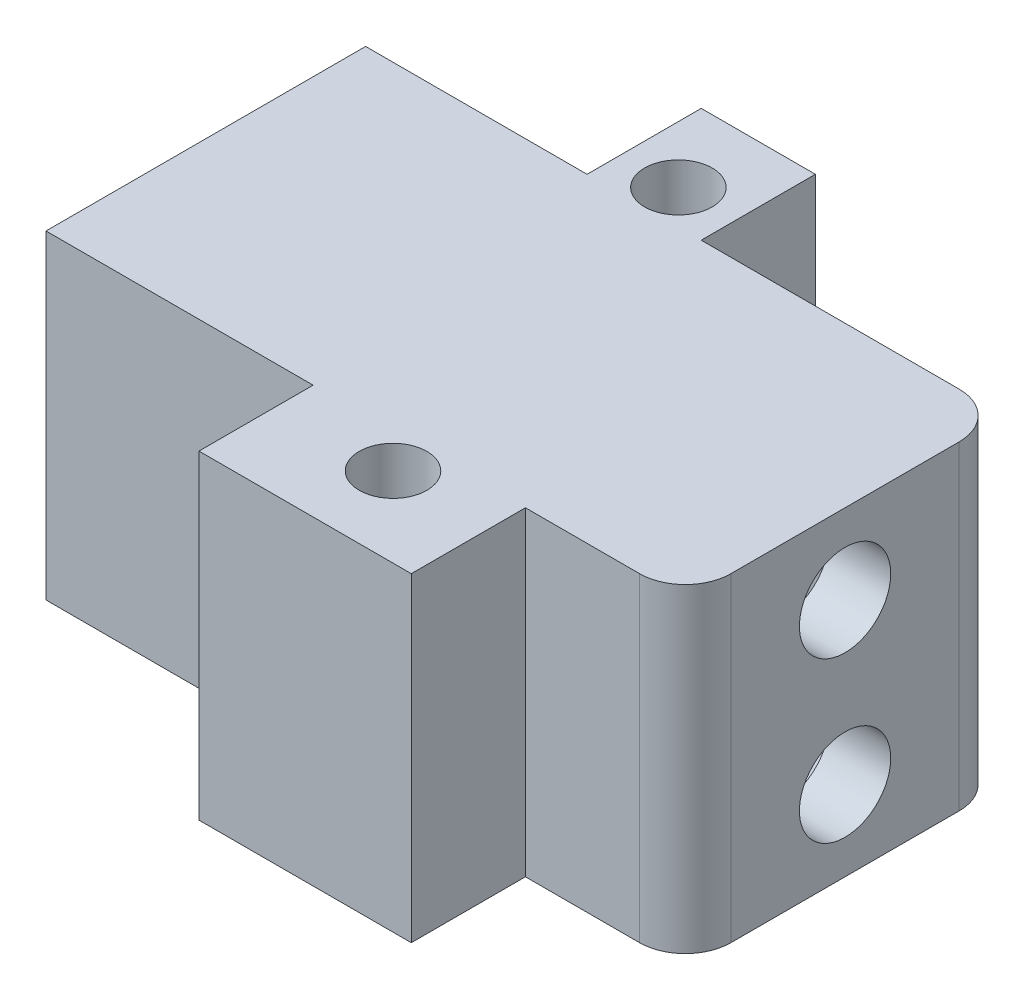
SolidWorks part; units mm, degrees
ref_plane "前视基准面" through (0, 0, 0) normal (0, 0, 1) x (1, 0, 0)
ref_plane "上视基准面" through (0, 0, 0) normal (0, 1, 0) x (1, 0, 0)
ref_plane "右视基准面" through (0, 0, 0) normal (1, 0, 0) x (0, 0, -1)
sketch "草图1" plane through (0, 0, 0) normal (0, 1, 0) x (1, 0, 0)
  line L1 (-14, 7) -> (14, 7)
  line L2 (-14, 7) -> (-14, -7)
  line L3 (-14, -7) -> (14, -7)
  line L4 (14, 7) -> (14, -7)
  line L5 (-14, 7) -> (14, -7) construction
  line L6 (-14, -7) -> (14, 7) construction
  point P0 (0, 0)
  dimension "D1" = 28
  dimension "D2" = 14
extrude "凸台-拉伸1" add sketch "草图1" along normal blind 14
sketch "草图2" plane through (-14, 0, 0) normal (-1, 0, 0) x (0, 0, 1)
  line L0 (-7, 14) -> (7, 0) construction
  line L1 (-7, 0) -> (7, 14) construction
  line L3 (-5, 13) -> (5, 13)
  line L4 (-7, 0) -> (7, 0)
  line L5 (7, 0) -> (7, 14)
  line L6 (7, 14) -> (-7, 14)
  line L7 (-7, 14) -> (-7, 0)
  line L8 (-7, 0) -> (7, 0)
  line L9 (7, 0) -> (7, 14)
  line L10 (7, 14) -> (-7, 14)
  line L11 (-7, 14) -> (-7, 0)
  line L12 (-5, 13) -> (-5, 1)
  line L13 (-5, 1) -> (5, 1)
  line L14 (5, 13) -> (5, 1)
  line L15 (-5, 13) -> (5, 1) construction
  line L16 (-5, 1) -> (5, 13) construction
  point P2 (0, 7)
  dimension "D2" = 12
  dimension "D3" = 10
  dimension "D1" = 0
extrude "切除-拉伸1" cut sketch "草图2" against normal blind 25.3 contours L12 L3 L14 L13
sketch "草图3" plane through (14, 0, 0) normal (1, 0, 0) x (0, 0, -1)
  line L0 (0, 14) -> (0, 0) construction
  line L2 (-7, 7) -> (7, 7)
  line L3 (-7, 7) -> (-7, 5.5)
  line L4 (-7, 0) -> (7, 0)
  line L5 (7, 0) -> (7, 14)
  line L6 (7, 14) -> (-7, 14)
  line L7 (-7, 14) -> (-7, 0)
  line L8 (-7, 0) -> (7, 0)
  line L9 (7, 0) -> (7, 14)
  line L10 (7, 14) -> (-7, 14)
  line L11 (-7, 14) -> (-7, 0)
  line L12 (-7, 5.5) -> (7, 5.5)
  line L13 (7, 7) -> (7, 5.5)
  line L14 (-7, 7) -> (7, 5.5) construction
  line L15 (-7, 5.5) -> (7, 7) construction
  circle A0 centre (0, 10.5) radius 2
  circle A1 centre (0, 3.5) radius 2
  point P10 (0, 6.25)
  dimension "D2" = 3.5
  dimension "D3" = 3.5
  dimension "D4" = 7
  dimension "D5" = 1.5
  dimension "D1" = 0
extrude "切除-拉伸2" cut sketch "草图3" against normal blind 25.5 contours A0 | A1
fillet "圆角4" radius 2 2 edges at (14, 7, -7) (14, 7, 7)
sketch "草图4" plane through (0, 0, 7) normal (0, 0, 1) x (1, 0, 0)
  line L0 (-14, 0) -> (12, 0) construction
  line L1 (-2.3, 0) -> (7, 0)
  line L2 (-2.3, 0) -> (-2.3, 14)
  line L3 (-2.3, 14) -> (7, 14)
  line L4 (7, 0) -> (7, 14)
  line L5 (-14, 14) -> (12, 14) construction
  line L6 (12, 0) -> (12, 14) construction
  dimension "D1" = 5
  dimension "D2" = 9.3
extrude "凸台-拉伸2" add sketch "草图4" along normal blind 5
sketch "草图5" plane through (0, 0, -7) normal (0, 0, -1) x (-1, 0, 0)
  line L1 (-0.7, 18) -> (-0.7, 13.5) construction
  line L2 (-0.7, 14) -> (4.3, 14)
  line L3 (-0.7, 14) -> (-0.7, 0)
  line L4 (14, 14) -> (-12, 14)
  line L5 (-12, 14) -> (-12, 0)
  line L6 (-12, 0) -> (14, 0)
  line L7 (14, 0) -> (14, 14)
  line L8 (14, 14) -> (-12, 14)
  line L9 (-12, 14) -> (-12, 0)
  line L10 (-12, 0) -> (14, 0)
  line L11 (14, 0) -> (14, 14)
  line L12 (-0.7, 0) -> (4.3, 0)
  line L13 (4.3, 14) -> (4.3, 0)
  line M7 (14, 14) -> (-12, 14)
  line M9 (-12, 0) -> (14, 0)
  dimension "D2" = 11.3
  dimension "D3" = 5
  dimension "D1" = 0
extrude "凸台-拉伸3" add sketch "草图5" along normal blind 5 contours L13 L3 M7 M9
sketch "草图6" plane through (0, 14, 0) normal (0, 1, 0) x (1, 0, 0)
  line L10 (-3.2378, 118.5) -> (-10.8877, 105.25)
  line L11 (-10.8877, 101.25) -> (-0.8, 83.7776)
  line L12 (14, -5) -> (14, 5)
  line L13 (12, 7) -> (0.7, 7)
  line L14 (0.7, 7) -> (0.7, 12)
  line L15 (0.7, 12) -> (-4.3, 12)
  line L16 (-4.3, 12) -> (-4.3, 7)
  line L17 (-4.3, 7) -> (-14, 7)
  line L18 (-14, 7) -> (-14, -7)
  line L19 (-14, -7) -> (-2.3, -7)
  line L20 (-2.3, -7) -> (-2.3, -12)
  line L21 (-2.3, -12) -> (7, -12)
  line L22 (7, -12) -> (7, -7)
  line L23 (7, -7) -> (12, -7)
  line L24 (14, -5) -> (14, 5)
  line L25 (12, 7) -> (0.7, 7)
  line L26 (0.7, 7) -> (0.7, 12)
  line L27 (0.7, 12) -> (-4.3, 12)
  line L28 (-4.3, 12) -> (-4.3, 7)
  line L29 (-4.3, 7) -> (-14, 7)
  line L30 (-14, 7) -> (-14, -7)
  line L31 (-14, -7) -> (-2.3, -7)
  line L32 (-2.3, -7) -> (-2.3, -12)
  line L33 (-2.3, -12) -> (7, -12)
  line L34 (7, -12) -> (7, -7)
  line L35 (7, -7) -> (12, -7)
  line L36 (-2.2641, 78.3135) -> (-9.3, 74.2513)
  line L37 (-9.3, 31.5) -> (-9.3, -15.5)
  line L38 (-9.3, -15.5) -> (52.7, -15.5)
  line L39 (52.7, -15.5) -> (52.7, 31.5)
  line L40 (52.7, 74.2513) -> (45.6641, 78.3135)
  line L41 (44.2, 83.7776) -> (54.2877, 101.25)
  line L42 (54.2877, 105.25) -> (46.6378, 118.5)
  line L43 (46.6378, 118.5) -> (-3.2378, 118.5)
  line L44 (-3.2378, 118.5) -> (-10.8877, 105.25)
  line L45 (-10.8877, 101.25) -> (-0.8, 83.7776)
  line L46 (-2.2641, 78.3135) -> (-9.3, 74.2513)
  line L47 (-9.3, 31.5) -> (-9.3, -15.5)
  line L48 (-9.3, -15.5) -> (52.7, -15.5)
  line L49 (52.7, -15.5) -> (52.7, 31.5)
  line L50 (52.7, 74.2513) -> (45.6641, 78.3135)
  line L51 (44.2, 83.7776) -> (54.2877, 101.25)
  line L52 (54.2877, 105.25) -> (46.6378, 118.5)
  line L53 (46.6378, 118.5) -> (-3.2378, 118.5)
  line L186 (-9.3, 74.2513) -> (-15.3, 71.5)
  line L187 (-9.3, 74.2513) -> (-15.3, 71.5)
  line L188 (-15.3, 71.5) -> (-15.3, 31.5)
  line L189 (-15.3, 71.5) -> (-15.3, 31.5)
  line L190 (-15.3, 31.5) -> (-9.3, 31.5)
  line L191 (-15.3, 31.5) -> (-9.3, 31.5)
  line L192 (52.7, 31.5) -> (58.7, 31.5)
  line L193 (52.7, 31.5) -> (58.7, 31.5)
  line L194 (58.7, 31.5) -> (58.7, 71.5)
  line L195 (58.7, 31.5) -> (58.7, 71.5)
  line L196 (58.7, 71.5) -> (52.7, 74.2513)
  line L197 (58.7, 71.5) -> (52.7, 74.2513)
  circle A0 centre (2.7, -8.5) radius 1.48
  arc A2 (14, 5) -> (12, 7) centre (12, 5) ccw
  arc A3 (12, -7) -> (14, -5) centre (12, -5) ccw
  arc A4 (14, 5) -> (12, 7) centre (12, 5) ccw
  arc A5 (12, -7) -> (14, -5) centre (12, -5) ccw
  circle A7 centre (-1.8, 8.5) radius 1.48 construction
  arc A8 (-10.8877, 105.25) -> (-10.8877, 101.25) centre (-7.4236, 103.25) ccw
  arc A9 (-2.2641, 78.3135) -> (-0.8, 83.7776) centre (-4.2641, 81.7776) ccw
  arc A10 (44.2, 83.7776) -> (45.6641, 78.3135) centre (47.6641, 81.7776) ccw
  arc A11 (54.2877, 101.25) -> (54.2877, 105.25) centre (50.8236, 103.25) ccw
  arc A12 (-10.8877, 105.25) -> (-10.8877, 101.25) centre (-7.4236, 103.25) ccw
  arc A13 (-2.2641, 78.3135) -> (-0.8, 83.7776) centre (-4.2641, 81.7776) ccw
  arc A14 (44.2, 83.7776) -> (45.6641, 78.3135) centre (47.6641, 81.7776) ccw
  arc A15 (54.2877, 101.25) -> (54.2877, 105.25) centre (50.8236, 103.25) ccw
  circle A16 centre (-1.8, 8.5) radius 1.48
  dimension "D3" = 7
  dimension "D4" = 12
  dimension "D1" = 0
  dimension "D2" = 0
extrude "切除-拉伸3" cut sketch "草图6" against normal blind 20 contours A0 | A16
